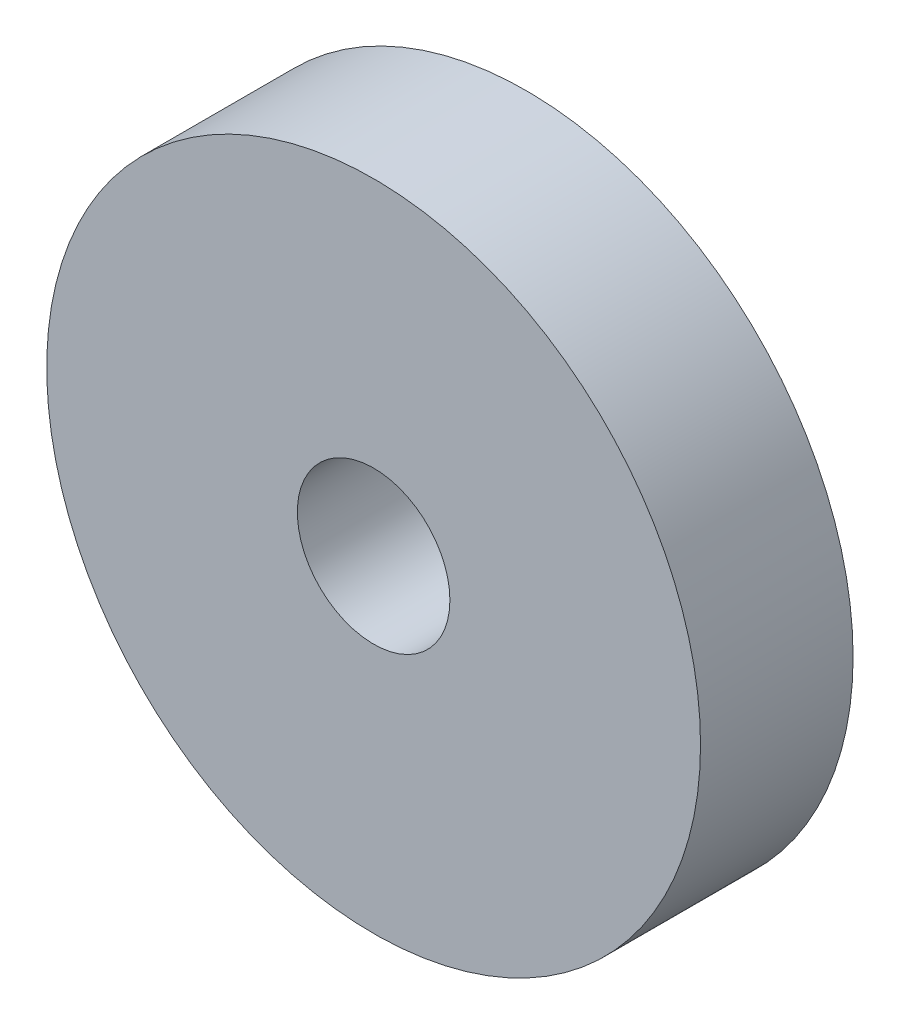
SolidWorks part; units mm, degrees
material "Beech"
ref_plane "Front Plane" through (0, 0, 0) normal (0, 0, 1) x (1, 0, 0)
ref_plane "Top Plane" through (0, 0, 0) normal (0, 1, 0) x (1, 0, 0)
ref_plane "Right Plane" through (0, 0, 0) normal (1, 0, 0) x (0, 0, -1)
sketch "Sketch1" plane through (0, 0, 0) normal (0, 0, 1) x (1, 0, 0)
  circle A0 centre (0, 0) radius 0.889
  circle A1 centre (0, 0) radius 3.81
  dimension "D1" = 7.62
  dimension "D2" = 1.778
extrude "Boss-Extrude1" add sketch "Sketch1" along normal blind 1.778
